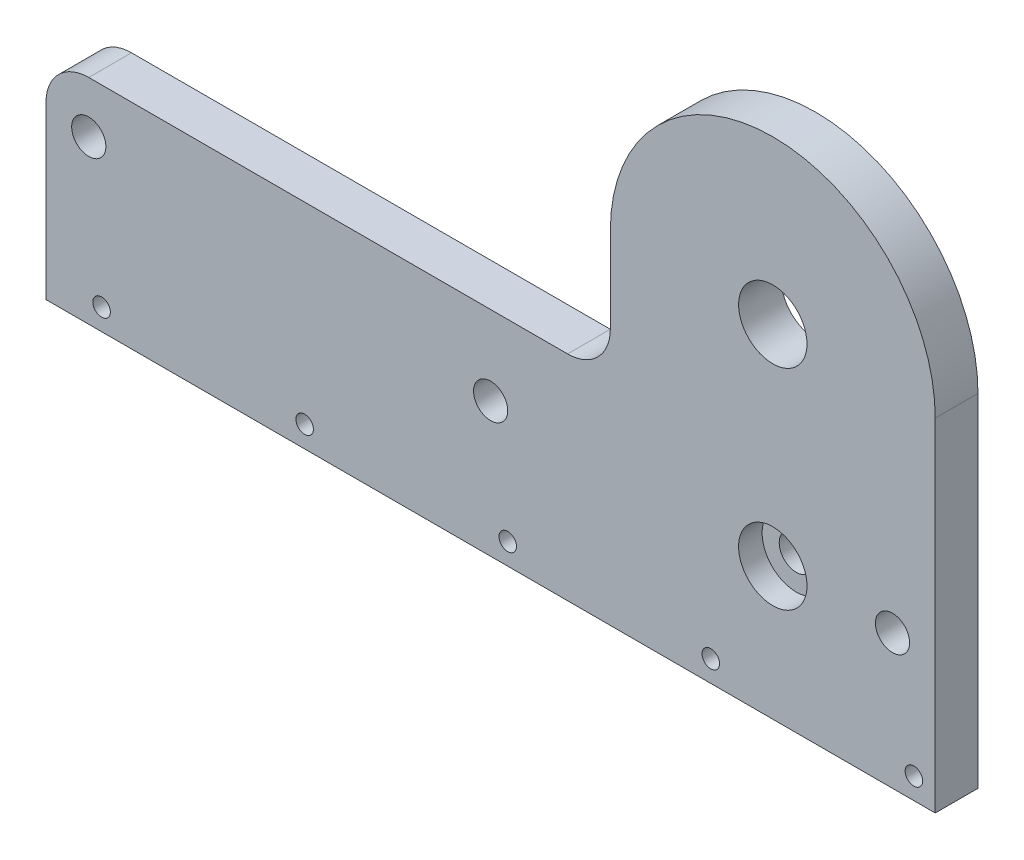
SolidWorks part; units mm, degrees
material "PTEG"
ref_plane "Alzado" through (0, 0, 0) normal (0, 0, 1) x (1, 0, 0)
ref_plane "Planta" through (0, 0, 0) normal (0, 1, 0) x (1, 0, 0)
ref_plane "Vista lateral" through (0, 0, 0) normal (1, 0, 0) x (0, 0, -1)
sketch "Croquis1" plane through (0, 0, 0) normal (0, 0, 1) x (1, 0, 0)
  line L0 (0, 0) -> (208, 0)
  line L1 (208, 0) -> (208, 80)
  line L2 (0, 0) -> (0, 40)
  line L3 (10, 50) -> (122, 50)
  line L4 (132, 60) -> (132, 80)
  arc A0 (208, 80) -> (132, 80) centre (170, 80) ccw
  arc A1 (0, 40) -> (10, 50) centre (10, 40) cw
  arc A2 (122, 50) -> (132, 60) centre (122, 60) ccw
  circle A3 centre (170, 80) radius 8
  circle A4 centre (170, 31) radius 8
  dimension "D4" = 80
  dimension "D5" = 10
  dimension "D6" = 16
  dimension "D7" = 16
  dimension "D1" = 50
  dimension "D2" = 208
  dimension "D3" = 76
  dimension "D8" = 31
extrude "Saliente-Extruir1" add sketch "Croquis1" against normal blind 10
sketch "Croquis2" plane through (0, 0, -10) normal (0, 0, -1) x (-1, 0, 0)
  line L0 (-208, 0) -> (-208, 80) construction
  line L1 (0, 0) -> (-208, 0) construction
  circle A0 centre (-203, 5) radius 2.05
  circle A1 centre (-155.5, 5) radius 2.05
  circle A2 centre (-108, 5) radius 2.05
  circle A3 centre (-60.5, 5) radius 2.05
  circle A4 centre (-13, 5) radius 2.05
  dimension "D2" = 5
  dimension "D3" = 4.1
  dimension "D1" = 5
  dimension "D4" = 5
extrude "Cortar-Extruir1" cut sketch "Croquis2" against normal through all
sketch "Croquis3" plane through (0, 0, -10) normal (0, 0, -1) x (-1, 0, 0)
  circle A0 centre (-170, 31) radius 8
  circle A1 centre (-170, 31) radius 4
  dimension "D1" = 8
extrude "Saliente-Extruir2" add sketch "Croquis3" against normal blind 4.5
sketch "Croquis4" plane through (0, 0, 0) normal (0, 0, 1) x (1, 0, 0)
  line L0 (208, 0) -> (208, 80) construction
  line L1 (122, 50) -> (10, 50) construction
  line L2 (0, 40) -> (0, 0) construction
  line L3 (0, 0) -> (208, 0) construction
  circle A0 centre (198, 31.4905) radius 4
  circle A1 centre (104, 31.4905) radius 4
  circle A2 centre (10, 38) radius 4
  point P13 (104, 0)
  dimension "D1" = 8
  dimension "D3" = 10
  dimension "D4" = 12
  dimension "D2" = 10
extrude "Cortar-Extruir2" cut sketch "Croquis4" against normal through all
